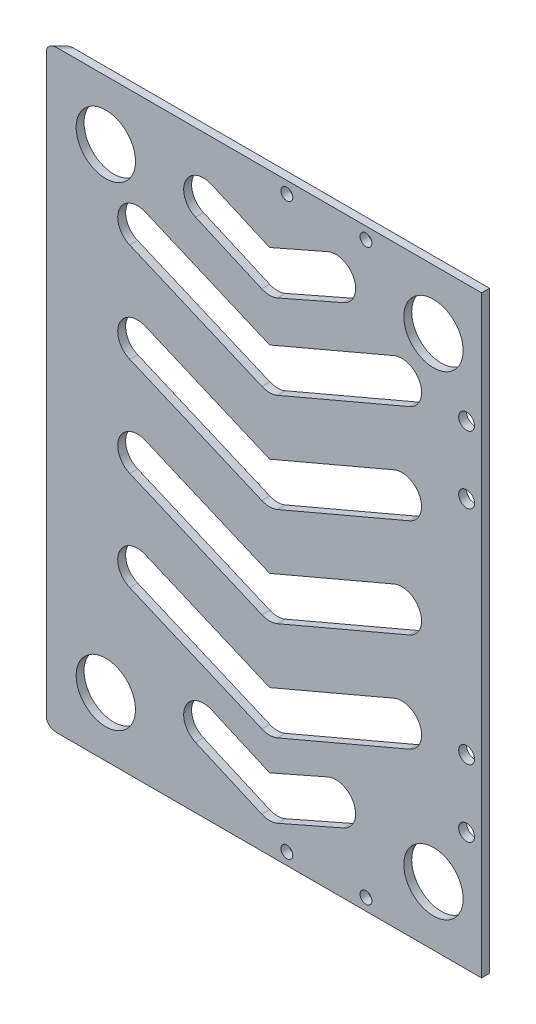
SolidWorks part; units mm, degrees
ref_plane "前视基准面" through (0, 0, 0) normal (0, 0, 1) x (1, 0, 0)
ref_plane "上视基准面" through (0, 0, 0) normal (0, 1, 0) x (1, 0, 0)
ref_plane "右视基准面" through (0, 0, 0) normal (1, 0, 0) x (0, 0, -1)
other "Configuration Table"
sketch "草图1" plane through (0, 0, 0) normal (0, 0, 1) x (1, 0, 0)
  line L1 (0, 0) -> (110, 0)
  line L2 (0, 0) -> (0, 150)
  line L3 (0, 150) -> (110, 150)
  line L4 (110, 0) -> (110, 150)
  dimension "D1" = 150
  dimension "D2" = 110
extrude "凸台-拉伸1" add sketch "草图1" along normal blind 2
sketch "草图2" plane through (0, 150, 0) normal (0, 1, 0) x (1, 0, 0)
  line L0 (0, -2) -> (0, 0)
  line L1 (0, 0) -> (2, 0)
  line L2 (110, 0) -> (0, 0) construction
  line L3 (2, 0) -> (0, -2)
extrude "切除-拉伸1" cut sketch "草图2" against normal through all
fillet "圆角1" radius 2 1 edges at (1, 150, 1)
fillet "圆角2" radius 2 1 edges at (1, 0, 1)
sketch "草图3" plane through (0, 0, 2) normal (0, 0, 1) x (1, 0, 0)
  line L0 (0, 75) -> (110, 75) construction
  line L1 (0, 148) -> (0, 2) construction
  line L2 (110, 0) -> (110, 150) construction
  line L3 (56.4142, 150) -> (56.4142, 0) construction
  line L4 (110, 150) -> (2.8284, 150) construction
  line L5 (2.8284, 0) -> (110, 0) construction
  circle A0 centre (106.2, 47) radius 2
  circle A1 centre (106.2, 30) radius 2
  circle A2 centre (106.2, 120) radius 2
  circle A3 centre (106.2, 103) radius 2
  dimension "D1" = 4
  dimension "D2" = 4
  dimension "D3" = 17
  dimension "D4" = 30
  dimension "D5" = 3.8
  dimension "D6" = 3.8
extrude "切除-拉伸2" cut sketch "草图3" against normal through all
sketch "草图4" plane through (0, 0, 0) normal (0, 0, -1) x (-1, 0, 0)
  circle A0 centre (-60.7609, 147) radius 1.5
  circle A1 centre (-80.7609, 147) radius 1.5
  dimension "D1" = 3
  dimension "D2" = 3
extrude "切除-拉伸3" cut sketch "草图4" against normal through all
sketch "草图5" plane through (0, 0, 0) normal (0, 0, -1) x (-1, 0, 0)
  circle A0 centre (-80.7613, 3) radius 1.5
  circle A1 centre (-60.7613, 3) radius 1.5
  dimension "D1" = 3
  dimension "D2" = 3
extrude "切除-拉伸4" cut sketch "草图5" against normal through all
sketch "草图6" plane through (0, 0, 2) normal (0, 0, 1) x (1, 0, 0)
  line L0 (110, 150) -> (2.8284, 150) construction
  line L1 (0, 148) -> (0, 2) construction
  line L2 (56.4142, 150) -> (56.4142, 0) construction
  line L5 (2.8284, 0) -> (110, 0) construction
  line L12 (0, 75) -> (110, 75) construction
  line L13 (110, 0) -> (110, 150) construction
  circle A0 centre (15, 135) radius 7.5
  circle A17 centre (15, 15) radius 7.5
  circle A18 centre (97.8284, 15) radius 7.5
  circle A19 centre (97.8284, 135) radius 7.5
  dimension "D1" = 15
  dimension "D2" = 15
  dimension "D3" = 15
extrude "切除-拉伸6" cut sketch "草图6" against normal blind 10
sketch "草图7" plane through (0, 0, 2) normal (0, 0, 1) x (1, 0, 0)
  line L0 (56.4142, 150) -> (56.4142, 0) construction
  line L1 (110, 150) -> (2.8284, 150) construction
  line L2 (2.8284, 0) -> (110, 0) construction
  line L3 (23.0098, 120.5807) -> (56.4142, 106.3528) construction
  line L4 (24.9691, 125.1808) -> (58.3735, 110.9529)
  line L5 (21.0505, 115.9806) -> (54.4549, 101.7527)
  line L6 (89.8186, 120.5807) -> (56.4142, 106.3528) construction
  line L7 (87.8593, 125.1808) -> (54.4549, 110.9529)
  line L8 (91.7779, 115.9806) -> (58.3735, 101.7527)
  line L9 (21.0505, 90.9806) -> (54.4549, 76.7527)
  line L10 (24.9691, 100.1808) -> (58.3735, 85.9529)
  line L11 (87.8593, 100.1808) -> (54.4549, 85.9529)
  line L12 (91.7779, 90.9806) -> (58.3735, 76.7527)
  line L13 (23.0098, 95.5807) -> (56.4142, 81.3528) construction
  line L14 (89.8186, 95.5807) -> (56.4142, 81.3528) construction
  line L15 (21.0505, 65.9806) -> (54.4549, 51.7527)
  line L16 (24.9691, 75.1808) -> (58.3735, 60.9529)
  line L17 (87.8593, 75.1808) -> (54.4549, 60.9529)
  line L18 (91.7779, 65.9806) -> (58.3735, 51.7527)
  line L19 (23.0098, 70.5807) -> (56.4142, 56.3528) construction
  line L20 (89.8186, 70.5807) -> (56.4142, 56.3528) construction
  line L21 (21.0505, 40.9806) -> (54.4549, 26.7527)
  line L22 (24.9691, 50.1808) -> (58.3735, 35.9529)
  line L23 (87.8593, 50.1808) -> (54.4549, 35.9529)
  line L24 (91.7779, 40.9806) -> (58.3735, 26.7527)
  line L25 (23.0098, 45.5807) -> (56.4142, 31.3528) construction
  line L26 (89.8186, 45.5807) -> (56.4142, 31.3528) construction
  line L27 (15, 135) -> (97.8284, 135) construction
  line L28 (0, 75) -> (110, 75) construction
  line L29 (0, 148) -> (0, 2) construction
  line L30 (110, 0) -> (110, 150) construction
  line L31 (39.6838, 135) -> (56.4142, 127.6638) construction
  line L32 (41.6917, 139.5791) -> (58.4221, 132.2429)
  line L33 (37.6759, 130.4209) -> (54.4063, 123.0847)
  line L34 (73.1446, 135) -> (56.4142, 127.6638) construction
  line L35 (71.1367, 139.5791) -> (54.4063, 132.2429)
  line L36 (75.1525, 130.4209) -> (58.4221, 123.0847)
  line L37 (37.6759, 15.4209) -> (54.4063, 8.0847)
  line L38 (41.6917, 24.5791) -> (58.4221, 17.2429)
  line L39 (71.1367, 24.5791) -> (54.4063, 17.2429)
  line L40 (75.1525, 15.4209) -> (58.4221, 8.0847)
  line L41 (39.6838, 20) -> (56.4142, 12.6638) construction
  line L42 (73.1446, 20) -> (56.4142, 12.6638) construction
  arc A0 (24.9691, 125.1808) -> (21.0505, 115.9806) centre (23.0098, 120.5807) ccw
  arc A1 (54.4549, 101.7527) -> (58.3735, 110.9529) centre (56.4142, 106.3528) ccw
  arc A2 (87.8593, 125.1808) -> (91.7779, 115.9806) centre (89.8186, 120.5807) cw
  arc A3 (58.3735, 101.7527) -> (54.4549, 110.9529) centre (56.4142, 106.3528) cw
  arc A4 (24.9691, 100.1808) -> (21.0505, 90.9806) centre (23.0098, 95.5807) ccw
  arc A5 (54.4549, 76.7527) -> (58.3735, 85.9529) centre (56.4142, 81.3528) ccw
  arc A6 (58.3735, 76.7527) -> (54.4549, 85.9529) centre (56.4142, 81.3528) cw
  arc A7 (87.8593, 100.1808) -> (91.7779, 90.9806) centre (89.8186, 95.5807) cw
  arc A8 (24.9691, 75.1808) -> (21.0505, 65.9806) centre (23.0098, 70.5807) ccw
  arc A9 (54.4549, 51.7527) -> (58.3735, 60.9529) centre (56.4142, 56.3528) ccw
  arc A10 (58.3735, 51.7527) -> (54.4549, 60.9529) centre (56.4142, 56.3528) cw
  arc A11 (87.8593, 75.1808) -> (91.7779, 65.9806) centre (89.8186, 70.5807) cw
  arc A12 (24.9691, 50.1808) -> (21.0505, 40.9806) centre (23.0098, 45.5807) ccw
  arc A13 (54.4549, 26.7527) -> (58.3735, 35.9529) centre (56.4142, 31.3528) ccw
  arc A14 (58.3735, 26.7527) -> (54.4549, 35.9529) centre (56.4142, 31.3528) cw
  arc A15 (87.8593, 50.1808) -> (91.7779, 40.9806) centre (89.8186, 45.5807) cw
  arc A16 (41.6917, 139.5791) -> (37.6759, 130.4209) centre (39.6838, 135) ccw
  arc A17 (54.4063, 123.0847) -> (58.4221, 132.2429) centre (56.4142, 127.6638) ccw
  arc A18 (71.1367, 139.5791) -> (75.1525, 130.4209) centre (73.1446, 135) cw
  arc A19 (58.4221, 123.0847) -> (54.4063, 132.2429) centre (56.4142, 127.6638) cw
  arc A20 (41.6917, 24.5791) -> (37.6759, 15.4209) centre (39.6838, 20) ccw
  arc A21 (54.4063, 8.0847) -> (58.4221, 17.2429) centre (56.4142, 12.6638) ccw
  arc A22 (58.4221, 8.0847) -> (54.4063, 17.2429) centre (56.4142, 12.6638) cw
  arc A23 (71.1367, 24.5791) -> (75.1525, 15.4209) centre (73.1446, 20) cw
  point P8 (39.712, 113.4668)
  point P16 (73.1164, 113.4668)
  point P23 (39.712, 88.4668)
  point P30 (73.1164, 88.4668)
  point P37 (39.712, 63.4668)
  point P44 (73.1164, 63.4668)
  point P51 (39.712, 38.4668)
  point P58 (73.1164, 38.4668)
  point P74 (48.049, 131.3319)
  point P82 (64.7794, 131.3319)
  point P89 (48.049, 16.3319)
  point P96 (64.7794, 16.3319)
  dimension "D1" = 5
  dimension "D3" = 5
  dimension "D2" = 4
  dimension "D4" = 2
extrude "切除-拉伸7" cut sketch "草图7" against normal blind 10 contours L33 A19 L35 L32 A16 | A19 A17 L32 L35 | A18 L35 L32 A17 L36 | A2 L7 L4 A1 L8 | A3 A1 L4 L7 | L5 A3 L7 L4 A0 | L9 A6 L11 L10 A4 | A6 A5 L10 L11 | A7 L11 L10 A5 L12 | A11 L17 L16 A9 L18 | A10 A9 L16 L17 | L15 A10 L17 L16 A8 | L21 A14 L23 L22 A12 | A14 A13 L22 L23 | A15 L23 L22 A13 L24 | A23 L39 L38 A21 L40 | A22 A21 L38 L39 | L37 A22 L39 L38 A20
